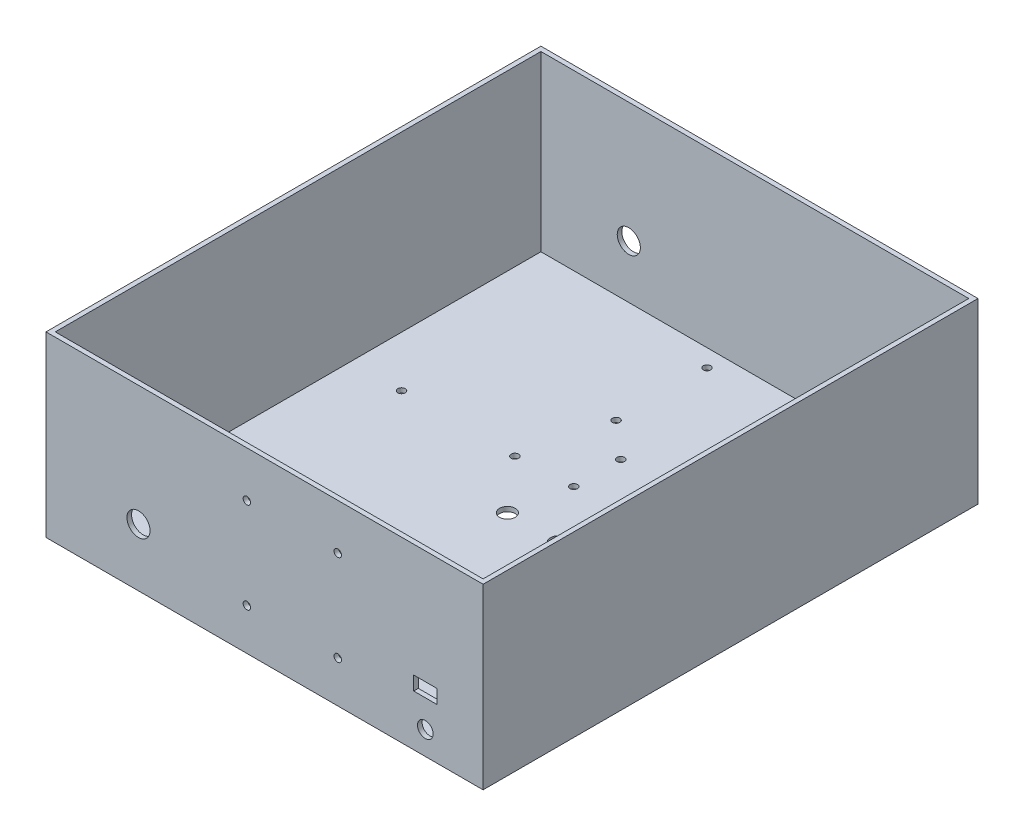
SolidWorks part; units mm, degrees
material "ABS"
ref_plane "Front Plane" through (0, 0, 0) normal (0, 0, 1) x (1, 0, 0)
ref_plane "Top Plane" through (0, 0, 0) normal (0, 1, 0) x (1, 0, 0)
ref_plane "Right Plane" through (0, 0, 0) normal (1, 0, 0) x (0, 0, -1)
sketch "Sketch2" plane through (0, 0, 0) normal (0, 1, 0) x (1, 0, 0)
  line L0 (-94.5, 107) -> (-94.5, -107)
  line L1 (-92.5, 105) -> (92.5, 105)
  line L2 (-92.5, 105) -> (-92.5, -105)
  line L3 (-92.5, -105) -> (92.5, -105)
  line L4 (92.5, 105) -> (92.5, -105)
  line L5 (-92.5, 105) -> (92.5, -105) construction
  line L6 (-92.5, -105) -> (92.5, 105) construction
  line L7 (-94.5, -107) -> (94.5, -107)
  line L8 (94.5, 107) -> (94.5, -107)
  line L9 (-94.5, 107) -> (94.5, 107)
  point P0 (0, 0)
  dimension "D1" = 210
  dimension "D2" = 185
  dimension "D3" = 2
extrude "Walls" add sketch "Sketch2" along normal blind 75
sketch "Sketch3" plane through (0, 0, 0) normal (0, -1, 0) x (1, 0, 0)
  line L1 (-94.5, -107) -> (94.5, -107)
  line L2 (-94.5, -107) -> (-94.5, 107)
  line L3 (-94.5, 107) -> (94.5, 107)
  line L4 (94.5, -107) -> (94.5, 107)
  line L5 (-94.5, -107) -> (94.5, 107) construction
  line L6 (-94.5, 107) -> (94.5, -107) construction
  point P0 (0, 0)
extrude "Base" add sketch "Sketch3" along normal blind 2
sketch "Sketch4" plane through (0, 0, -107) normal (0, 0, -1) x (-1, 0, 0)
  line L0 (94.5, -2) -> (-94.5, -2) construction
  line L3 (94.5, 75) -> (94.5, -2) construction
  line L4 (-74.5, 20) -> (-64.5, 20)
  line L5 (-74.5, 20) -> (-74.5, 26)
  line L6 (-74.5, 26) -> (-64.5, 26)
  line L7 (-64.5, 20) -> (-64.5, 26)
  line L8 (-74.5, 20) -> (-64.5, 26) construction
  line L9 (-74.5, 26) -> (-64.5, 20) construction
  line L10 (-94.5, 75) -> (-94.5, -2) construction
  circle A1 centre (54.5, 23) radius 5
  point P0 (-69.5, 23)
  dimension "D1" = 25
  dimension "D2" = 10
  dimension "D3" = 25
  dimension "D4" = 6
  dimension "D5" = 40
  dimension "D6" = 10
extrude "Cut-Extrude1" cut sketch "Sketch4" against normal through all
sketch "Sketch5" plane through (0, 0, -107) normal (0, 0, -1) x (-1, 0, 0)
  circle A0 centre (-69.5, 8.0963) radius 3.3782 construction
  circle A1 centre (-69.5, 8.0963) radius 3.3782
extrude "Cut-Extrude2" cut sketch "Sketch5" against normal through all
hole_wizard "1/4 Clearance Hole1" positions "Sketch7" profile "Sketch8" hole size "1/4" standard "ANSI Inch" end condition through all
sketch "Sketch7" plane through (0, -2, 0) normal (0, -1, 0) x (-1, 0, 0)
  line L0 (0, 0) -> (-94.5, 0) construction
  line L1 (-94.5, 107) -> (-94.5, -107) construction
  point P0 (-20, 0)
  point P2 (2, 0)
  dimension "D1" = 20
  dimension "D2" = 22
sketch "Sketch8" plane through (20, -2, 0) normal (1, 0, 0) x (0, 0, -1)
  line L0 (0, 0) -> (0, 77)
  line L1 (0, 77) -> (3.3782, 77)
  line L2 (3.3782, 77) -> (3.3782, 0)
  line L5 (3.3782, 0) -> (0, 0)
  line L11 (0, -6.35) -> (0, 107.95) construction
  dimension "Thru Hole Dia." = 6.7564
  dimension "Thru Hole Depth" = 77
sketch "Sketch9" plane through (0, -2, 0) normal (0, -1, 0) x (1, 0, 0)
  circle A0 centre (82.9, 61.675) radius 1.6
  circle A1 centre (82.9, -61.675) radius 1.6
  circle A2 centre (39.9, 61.675) radius 1.6
  circle A3 centre (39.9, -61.675) radius 1.6
  circle A4 centre (26.1708, -58.1418) radius 1.6
  circle A5 centre (26.1708, -97.4418) radius 1.6
  circle A6 centre (-13.1292, -58.1418) radius 1.6
  circle A7 centre (-13.1292, -97.4418) radius 1.6
  circle A8 centre (22.8415, -24.1852) radius 1.6
  circle A9 centre (22.8415, -44.4852) radius 1.6
  circle A10 centre (2.5415, -24.1852) radius 1.6
  circle A11 centre (2.5415, -44.4852) radius 1.6
  circle A12 centre (-21.5834, 35.1751) radius 1.6
  circle A13 centre (-21.5834, -22.8249) radius 1.6
  circle A14 centre (-70.5834, -22.8249) radius 1.6
  circle A15 centre (-70.5834, 35.1751) radius 1.6
  circle A16 centre (-58.8569, 58.6375) radius 1.6
  circle A17 centre (-19.5569, 58.6375) radius 1.6
  circle A18 centre (-19.5569, 97.9375) radius 1.6
  circle A19 centre (-58.8569, 97.9375) radius 1.6
  dimension "D1" = 3.2
sketch "Sketch10" plane through (0, 0, 107) normal (0, 0, 1) x (1, 0, 0)
  circle A0 centre (-7.6501, 55.256) radius 1.6
  circle A1 centre (31.6499, 55.256) radius 1.6
  circle A2 centre (31.6499, 15.956) radius 1.6
  circle A3 centre (-7.6501, 15.956) radius 1.6
  point P12 (0, 0)
  dimension "D1" = 3.2
extrude "Cut-Extrude3" cut sketch "Sketch9" against normal up to next
extrude "Cut-Extrude4" cut sketch "Sketch10" against normal up to next
